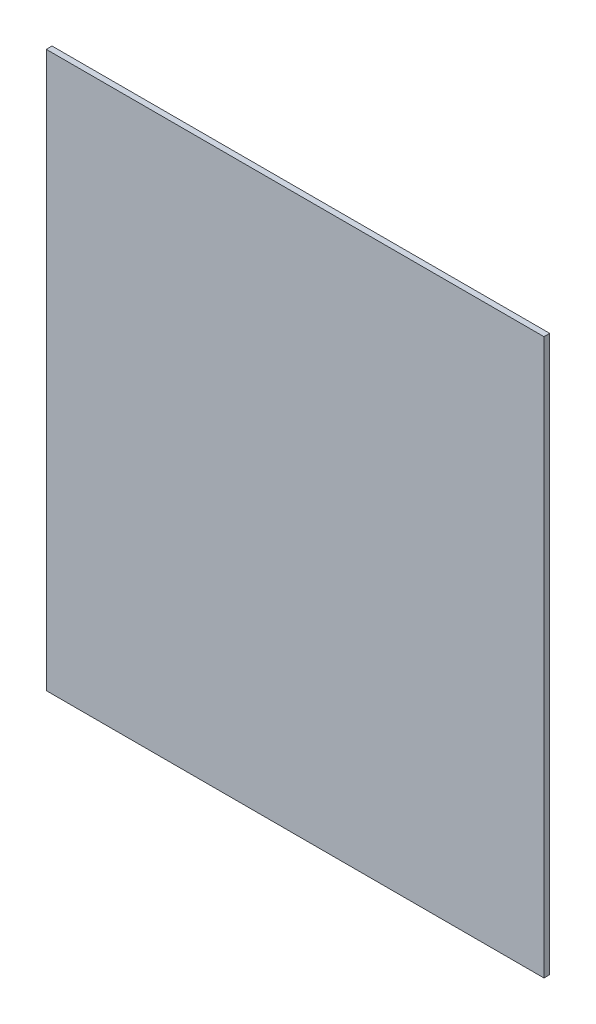
SolidWorks part; units mm, degrees
ref_plane "Plano frontal" through (0, 0, 0) normal (0, 0, 1) x (1, 0, 0)
ref_plane "Plano superior" through (0, 0, 0) normal (0, 1, 0) x (1, 0, 0)
ref_plane "Plano direito" through (0, 0, 0) normal (1, 0, 0) x (0, 0, -1)
sketch "Esboço1" plane through (0, 0, 0) normal (0, 0, 1) x (1, 0, 0)
  line L1 (34.5, -38.5) -> (-34.5, -38.5)
  line L2 (34.5, -38.5) -> (34.5, 38.5)
  line L3 (34.5, 38.5) -> (-34.5, 38.5)
  line L4 (-34.5, -38.5) -> (-34.5, 38.5)
  line L5 (34.5, -38.5) -> (-34.5, 38.5) construction
  line L6 (34.5, 38.5) -> (-34.5, -38.5) construction
  point P0 (0, 0)
  dimension "D1" = 69
  dimension "D2" = 77
extrude "Ressalto-extrusão1" add sketch "Esboço1" along normal blind 0.8
